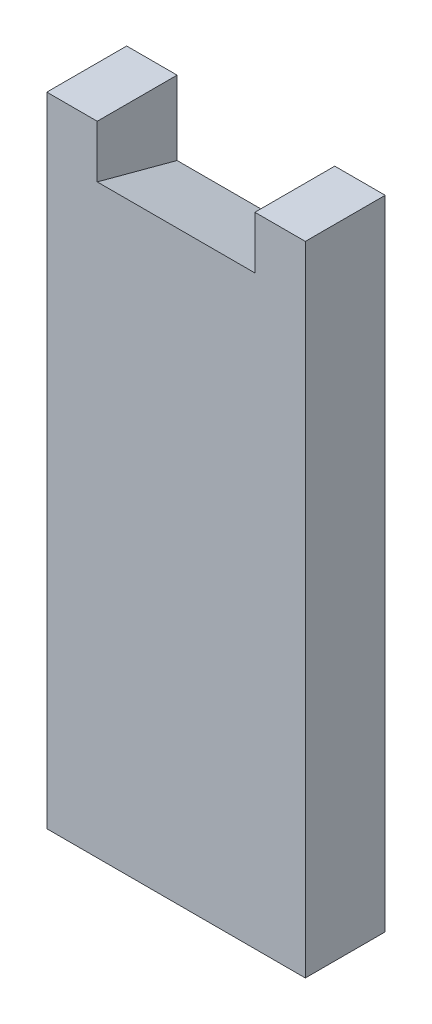
SolidWorks part; units mm, degrees
ref_plane "前视基准面" through (0, 0, 0) normal (0, 0, 1) x (1, 0, 0)
ref_plane "上视基准面" through (0, 0, 0) normal (0, 1, 0) x (1, 0, 0)
ref_plane "右视基准面" through (0, 0, 0) normal (1, 0, 0) x (0, 0, -1)
sketch "草图1" plane through (0, 0, 0) normal (0, 0, 1) x (1, 0, 0)
  line L1 (0, 0) -> (24.6, 0)
  line L2 (0, 0) -> (0, -60.7)
  line L3 (0, -60.7) -> (24.6, -60.7)
  line L4 (24.6, 0) -> (24.6, -60.7)
  line L5 (4.8, 0) -> (19.8, 0)
  line L6 (4.8, 0) -> (4.8, -5)
  line L7 (4.8, -5) -> (19.8, -5)
  line L8 (19.8, 0) -> (19.8, -5)
  point P9 (12.3, 0)
  dimension "D1" = 5
  dimension "D2" = 24.6
  dimension "D3" = 15
  dimension "D4" = 55.7
extrude "凸台-拉伸1" add sketch "草图1" along normal blind 7.6 contours L1 L8 L7 L6 L2 L3 L4
draft "拔模5" type of draft neutral plane draft angle 15 faces to draft 1 face at (12.3, -5, 3.8) neutral plane through (0, 0, 7.6) neutral plane normal (0, 0, 1) reverse direction yes parameters "D1"=15
